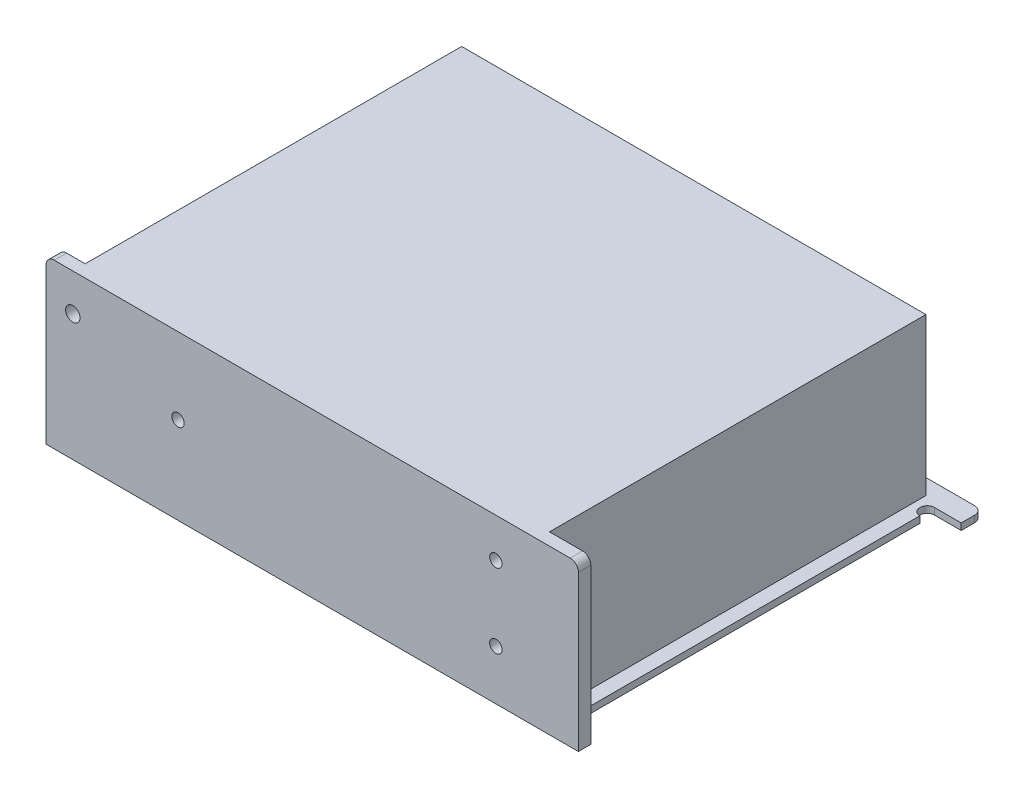
SolidWorks part; units mm, degrees
ref_plane "Front Plane" through (0, 0, 0) normal (0, 0, 1) x (1, 0, 0)
ref_plane "Top Plane" through (0, 0, 0) normal (0, 1, 0) x (1, 0, 0)
ref_plane "Right Plane" through (0, 0, 0) normal (1, 0, 0) x (0, 0, -1)
sketch "Sketch1" plane through (0, 0, 0) normal (0, 1, 0) x (1, 0, 0)
  line L0 (-68.0197, 49) -> (-68.0197, -49)
  line L1 (-68.0197, 49) -> (60.9803, 49)
  line L2 (54.4803, 49) -> (54.4803, -49) construction
  line L3 (-68.0197, -49) -> (60.9803, -49)
  line L4 (54.4803, 43.75) -> (60.9803, 43.75)
  line L5 (60.9803, 43.75) -> (60.9803, 49)
  line L6 (54.4803, -46) -> (60.9803, -46)
  line L7 (60.9803, -46) -> (60.9803, -49)
  line L8 (54.4803, 40.25) -> (54.4803, -46)
  arc A0 (54.4803, 43.75) -> (54.4803, 40.25) centre (54.4803, 42) ccw
  point P2 (-68.0197, 0)
  dimension "D4" = 122.5
  dimension "D6" = 1.75
  dimension "D1" = 98
  dimension "D2" = 0
  dimension "D3" = 129
  dimension "D5" = 7
extrude "Boss-Extrude1" add sketch "Sketch1" along normal blind 1.6
sketch "Sketch2" plane through (0, 1.6, 0) normal (0, 1, 0) x (1, 0, 0)
  line L0 (-68.0197, 49) -> (-68.0197, -49) construction
  line L1 (-61.5197, 45.2099) -> (50.9803, 45.2099)
  line L2 (-61.5197, 45.2099) -> (-61.5197, -46)
  line L3 (-61.5197, -46) -> (50.9803, -46)
  line L4 (50.9803, 45.2099) -> (50.9803, -46)
  line L5 (60.9803, -46) -> (54.4803, -46) construction
  point P6 (57.7303, -46)
  dimension "D1" = 112.5
  dimension "D2" = 6.5
  dimension "D3" = 0
extrude "Boss-Extrude2" add sketch "Sketch2" along normal blind 38
sketch "Sketch3" plane through (0, 1.6, 0) normal (0, 1, 0) x (1, 0, 0)
  line L1 (60.9803, -46) -> (-68.0197, -46)
  line L2 (60.9803, -46) -> (60.9803, -49)
  line L3 (60.9803, -49) -> (-68.0197, -49)
  line L4 (-68.0197, -46) -> (-68.0197, -49)
extrude "Boss-Extrude3" add sketch "Sketch3" along normal blind 38
sketch "Sketch4" plane through (0, 0, 49) normal (0, 0, 1) x (1, 0, 0)
  line L0 (-68.0197, 39.6) -> (60.9803, 39.6) construction
  line L1 (-68.0197, 39.6) -> (-68.0197, 0) construction
  circle A0 centre (-36.0197, 21.1) radius 1.5
  circle A1 centre (40.9803, 12.1) radius 1.5
  circle A2 centre (40.9803, 30.1) radius 1.5
  circle A3 centre (-61.5197, 30.6) radius 1.75
  dimension "D1" = 3
  dimension "D2" = 18.5
  dimension "D3" = 32
  dimension "D4" = 3
  dimension "D5" = 3
  dimension "D6" = 9
  dimension "D7" = 9
  dimension "D8" = 77
  dimension "D9" = 77
  dimension "D10" = 3.5
  dimension "D11" = 6.5
  dimension "D12" = 9
extrude "Cut-Extrude1" cut sketch "Sketch4" against normal blind 4
sketch "Sketch5" plane through (0, 0, 0) normal (0, -1, 0) x (1, 0, 0)
  line L0 (60.9803, -49) -> (-68.0197, -49) construction
  line L1 (-68.0197, -49) -> (-68.0197, 49) construction
  line L2 (-68.0197, 49) -> (60.9803, 49) construction
  circle A0 centre (-63.5197, 43.5) radius 1.75
  circle A1 centre (9.9803, 18) radius 1.5
  circle A2 centre (9.9803, -15) radius 1.5
  dimension "D1" = 3.5
  dimension "D2" = 92.5
  dimension "D3" = 4.5
  dimension "D4" = 3
  dimension "D5" = 3
  dimension "D6" = 73.5
  dimension "D7" = 73.5
  dimension "D8" = 33
  dimension "D9" = 31
extrude "Cut-Extrude2" cut sketch "Sketch5" against normal blind 4
fillet "Fillet1" radius 2 1 edges at (60.9803, 0.8, -49)
fillet "Fillet2" radius 2 1 edges at (60.9803, 39.6, 47.5)
fillet "Fillet3" radius 2 1 edges at (-68.0197, 39.6, 47.5)
